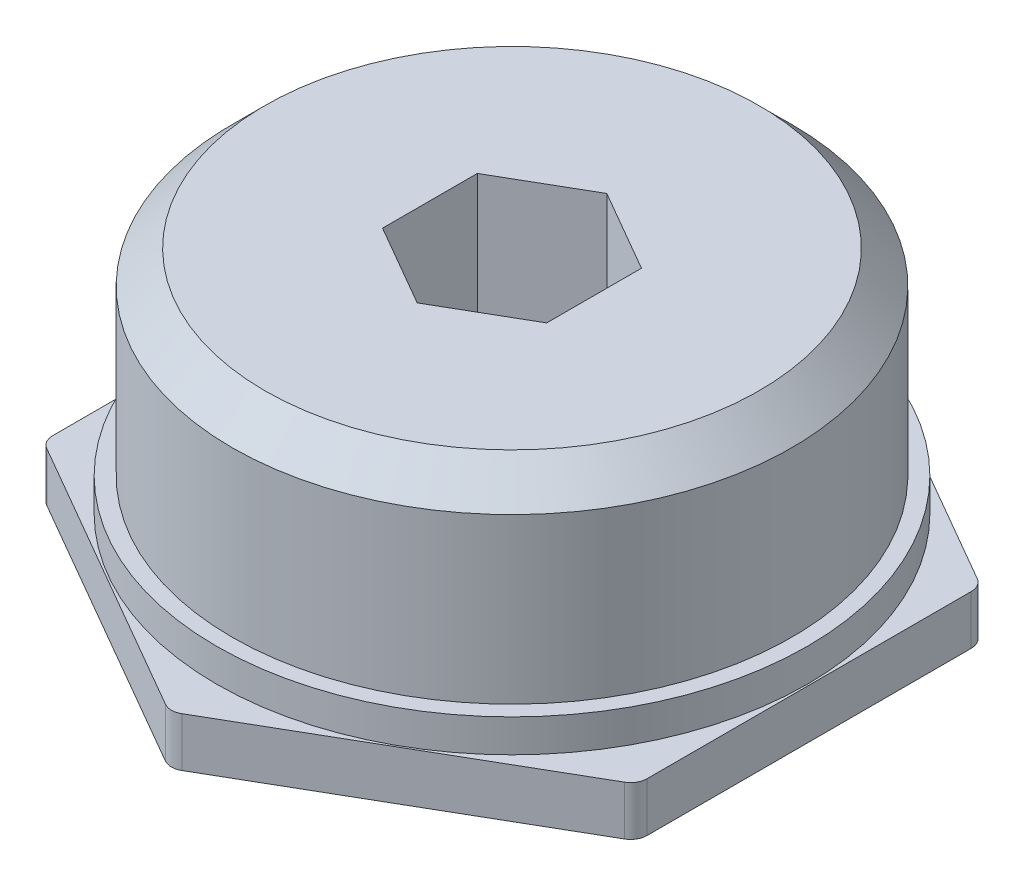
SolidWorks part; units mm, degrees
material "ABS"
ref_plane "Front Plane" through (0, 0, 0) normal (0, 0, 1) x (1, 0, 0)
ref_plane "Top Plane" through (0, 0, 0) normal (0, 1, 0) x (1, 0, 0)
ref_plane "Right Plane" through (0, 0, 0) normal (1, 0, 0) x (0, 0, -1)
ref_plane "Plane2" through (0, 31, 0) normal (0, 1, 0) x (1, 0, 0)
sketch "Sketch1" plane through (0, 31, 0) normal (0, 1, 0) x (1, 0, 0)
  line L1 (0, 10.45) -> (-9.05, 5.225)
  line L2 (-9.05, 5.225) -> (-9.05, -5.225)
  line L3 (-9.05, -5.225) -> (0, -10.45)
  line L4 (0, -10.45) -> (9.05, -5.225)
  line L5 (9.05, -5.225) -> (9.05, 5.225)
  line L6 (9.05, 5.225) -> (0, 10.45)
  circle A0 centre (0, 0) radius 9.05 construction
  dimension "D1" = 18.1
extrude "Boss-Extrude1" add sketch "Sketch1" along normal blind 1.5
fillet "Fillet1" radius 0.5 6 edges at (0, 31.75, -10.45) (-9.05, 31.75, -5.225) (-9.05, 31.75, 5.225) (0, 31.75, 10.45) (9.05, 31.75, 5.225) (9.05, 31.75, -5.225)
sketch "Sketch2" plane through (0, 32.5, 0) normal (0, 1, 0) x (1, 0, 0)
  circle A1 centre (0, 0) radius 9
  dimension "D2" = 18
extrude "Boss-Extrude2" add sketch "Sketch2" along normal blind 1 contours A1
sketch "Sketch3" plane through (0, 33.5, 0) normal (0, 1, 0) x (1, 0, 0)
  circle A0 centre (0, 0) radius 8.525
  dimension "D1" = 17.05
extrude "Boss-Extrude3" add sketch "Sketch3" along normal blind 4
sketch "Sketch5" plane through (0, 37.5, 0) normal (0, 1, 0) x (1, 0, 0)
  circle A0 centre (0, 0) radius 8.525
  circle A1 centre (0, 0) radius 8.525 construction
extrude "Boss-Extrude4" add sketch "Sketch5" along normal blind 1 and the other way blind 1
sketch "Sketch6" plane through (0, 38.5, 0) normal (0, 1, 0) x (1, 0, 0)
  circle A1 centre (0, 0) radius 8.525
  circle A2 centre (0, 0) radius 8.525 construction
extrude "Boss-Extrude5" add sketch "Sketch6" along normal blind 1
chamfer "Chamfer2" distance 1 angle 45 1 edges at (0, 39.5, 8.525)
sketch "Sketch4" plane through (0, 31, 0) normal (0, 1, 0) x (1, 0, 0)
  line L1 (0, 2.8868) -> (-2.5, 1.4434)
  line L2 (-2.5, 1.4434) -> (-2.5, -1.4434)
  line L3 (-2.5, -1.4434) -> (0, -2.8868)
  line L4 (0, -2.8868) -> (2.5, -1.4434)
  line L5 (2.5, -1.4434) -> (2.5, 1.4434)
  line L6 (2.5, 1.4434) -> (0, 2.8868)
  circle A0 centre (0, 0) radius 2.5 construction
  dimension "D1" = 5
extrude "Cut-Extrude1" cut sketch "Sketch4" along normal through all
